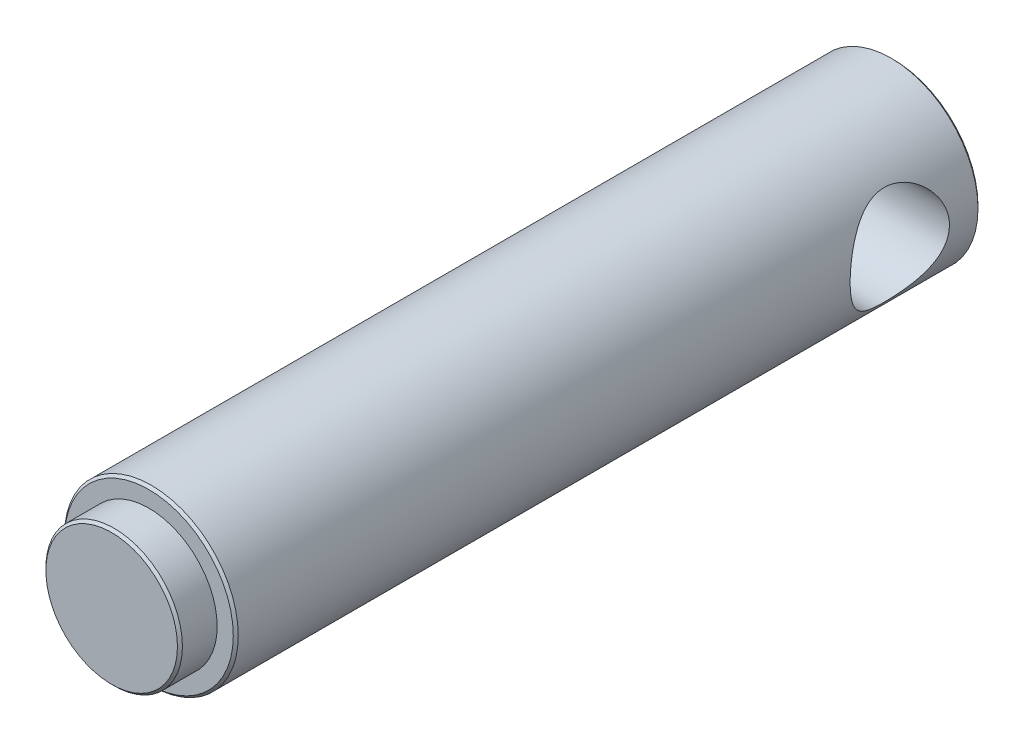
SolidWorks part; units mm, degrees
ref_plane "Ebene vorne" through (0, 0, 0) normal (0, 0, 1) x (1, 0, 0)
ref_plane "Ebene oben" through (0, 0, 0) normal (0, 1, 0) x (1, 0, 0)
ref_plane "Ebene rechts" through (0, 0, 0) normal (1, 0, 0) x (0, 0, -1)
sketch "Skizze1" plane through (0, 0, 0) normal (0, 0, 1) x (1, 0, 0)
  circle A0 centre (0, 0) radius 7
  dimension "D1" = 14
extrude "Aufsatz-Linear austragen1" add sketch "Skizze1" along normal blind 60
sketch "Skizze2" plane through (0, 0, 60) normal (0, 0, 1) x (1, 0, 0)
  circle A0 centre (0, 0) radius 5.5
  dimension "D1" = 11
extrude "Aufsatz-Linear austragen2" add sketch "Skizze2" along normal blind 3
sketch "Skizze4" plane through (0, 0, 0) normal (1, 0, 0) x (0, 0, -1)
  circle A0 centre (-6.5, 0) radius 4
  dimension "D1" = 6.5
  dimension "D2" = 8
extrude "Schnitt-Linear austragen2" cut sketch "Skizze4" against normal through all both and the other way through all
chamfer "Fase1" distance 0.2 angle 45 3 edges at (7, 0, 60) (5.5, 0, 63) (7, 0, 0)
